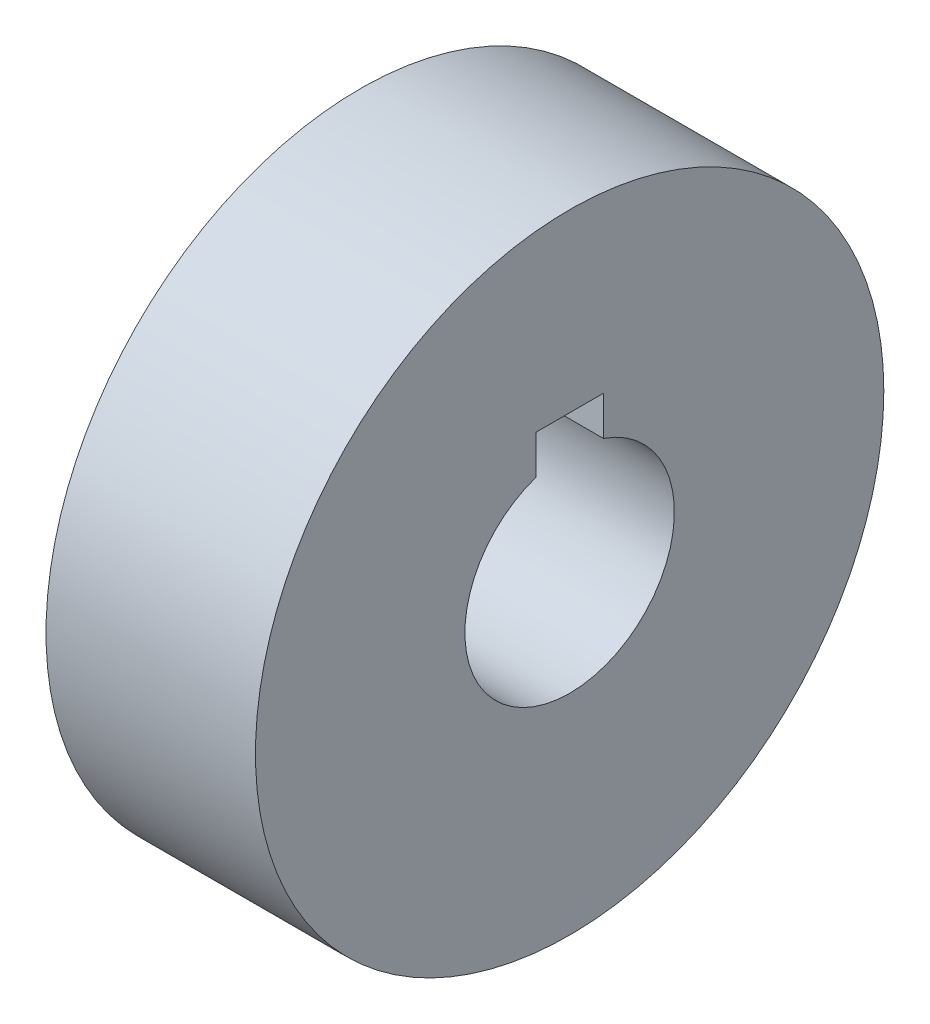
SolidWorks part; units mm, degrees
ref_plane "Front Plane" through (0, 0, 0) normal (0, 0, 1) x (1, 0, 0)
ref_plane "Top Plane" through (0, 0, 0) normal (0, 1, 0) x (1, 0, 0)
ref_plane "Right Plane" through (0, 0, 0) normal (1, 0, 0) x (0, 0, -1)
sketch "Sketch1" plane through (0, 0, 0) normal (1, 0, 0) x (0, 0, -1)
  line L0 (0, 55) -> (0, -55) construction
  line L1 (1.6151, 2.3316) -> (-1.6151, 2.3316)
  line L2 (1.6151, 2.3316) -> (1.6151, 6.6)
  line L3 (1.6151, 6.6) -> (-1.6151, 6.6)
  line L4 (-1.6151, 2.3316) -> (-1.6151, 6.6)
  line L5 (1.6151, 2.3316) -> (-1.6151, 6.6) construction
  line L6 (1.6151, 6.6) -> (-1.6151, 2.3316) construction
  line L7 (-15.6914, 5) -> (17.3965, 5) construction
  circle A0 centre (0, 0) radius 15
  circle A1 centre (0, 0) radius 5
  point P4 (0, 4.4658)
  dimension "D1" = 30
  dimension "D2" = 10
  dimension "D3" = 1.6
extrude "Boss-Extrude1" add sketch "Sketch1" along normal blind 10 contours A0 A1 L4 L3 L2
